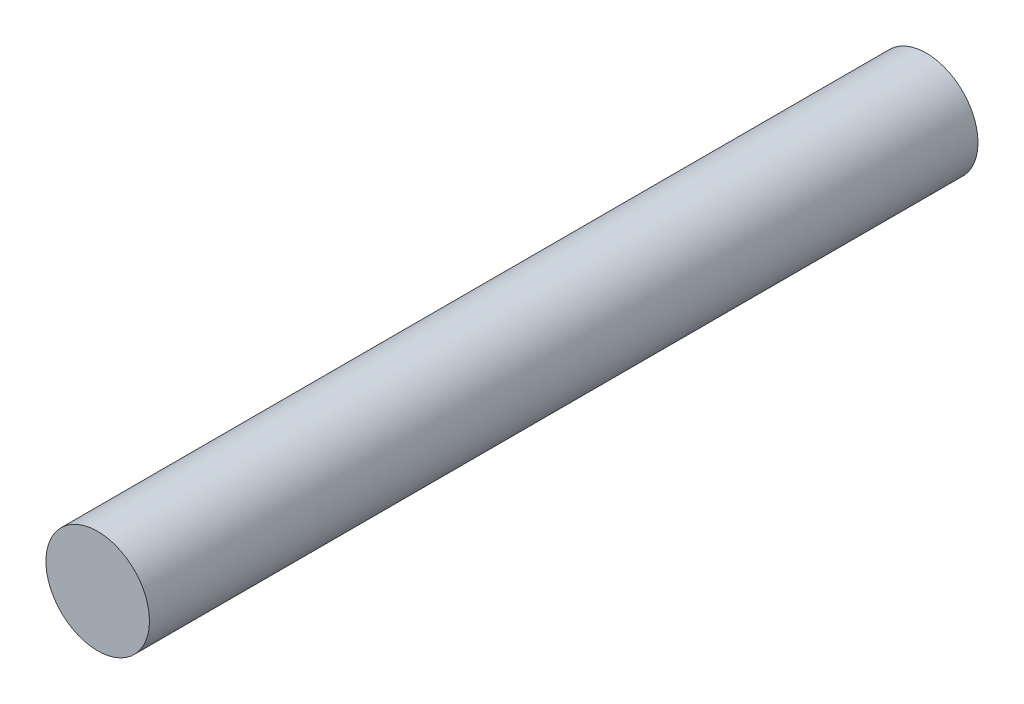
SolidWorks part; units mm, degrees
material "AISI 4340 Steel, normalized"
ref_plane "Front Plane" through (0, 0, 0) normal (0, 0, 1) x (1, 0, 0)
ref_plane "Top Plane" through (0, 0, 0) normal (0, 1, 0) x (1, 0, 0)
ref_plane "Right Plane" through (0, 0, 0) normal (1, 0, 0) x (0, 0, -1)
sketch "Sketch1" plane through (0, 0, 0) normal (0, 0, 1) x (1, 0, 0)
  circle A0 centre (0, 0) radius 0.5
extrude "Installed_D1x8_Coiled_Pin_Envelope" add sketch "Sketch1" along normal blind 8 from offset 4
